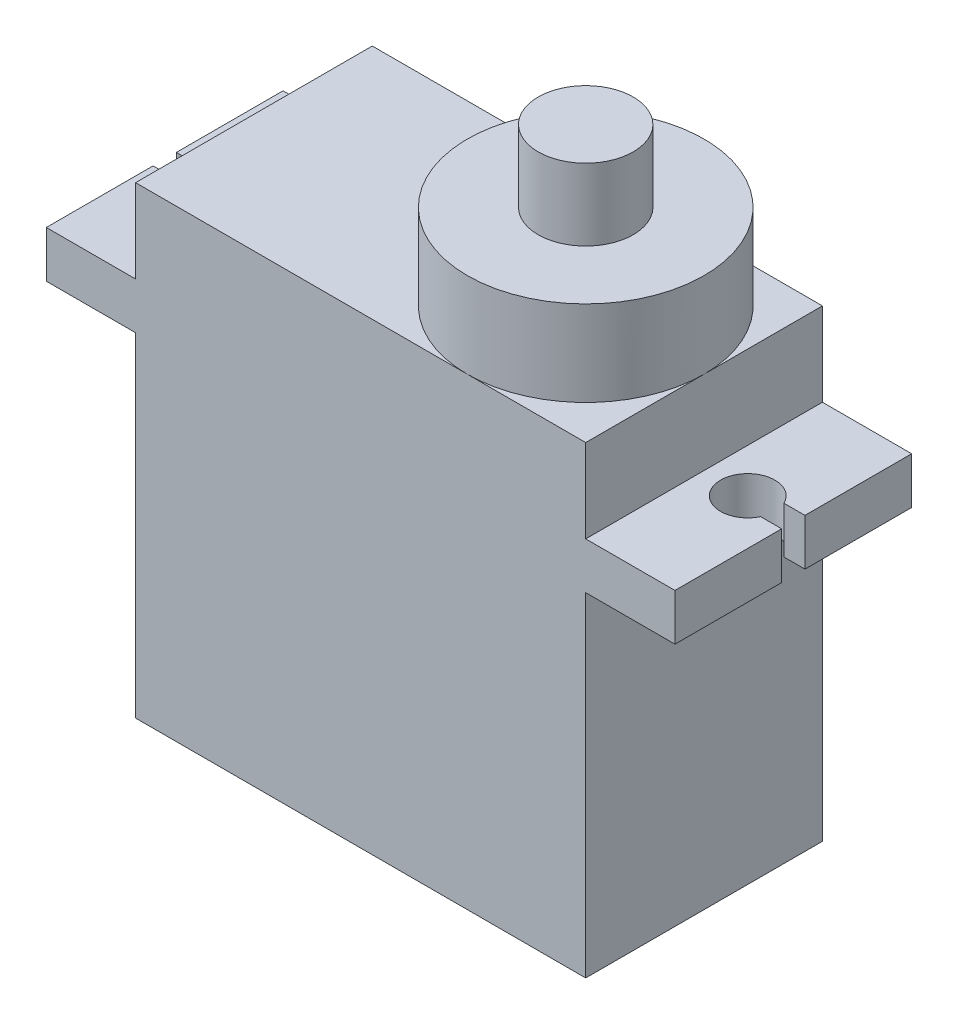
SolidWorks part; units mm, degrees
ref_plane "Front Plane" through (0, 0, 0) normal (0, 0, 1) x (1, 0, 0)
ref_plane "Top Plane" through (0, 0, 0) normal (0, 1, 0) x (1, 0, 0)
ref_plane "Right Plane" through (0, 0, 0) normal (1, 0, 0) x (0, 0, -1)
sketch "Sketch1" plane through (0, 0, 0) normal (0, 0, 1) x (1, 0, 0)
  line L1 (-4.0826, 11.0523) -> (19.1174, 11.0523)
  line L2 (-4.0826, 11.0523) -> (-4.0826, -6.1477)
  line L3 (-4.0826, -6.1477) -> (19.1174, -6.1477)
  line L4 (19.1174, 11.0523) -> (19.1174, -6.1477)
  dimension "D1" = 23.2
  dimension "D2" = 17.2
extrude "Boss-Extrude1" add sketch "Sketch1" along normal blind 12.2
sketch "Sketch2" plane through (0, 11.0523, 0) normal (0, 1, 0) x (1, 0, 0)
  line L0 (7.5174, 0) -> (7.5174, -12.2) construction
  line L1 (-8.6826, 0) -> (23.7174, 0)
  line L2 (-8.6826, 0) -> (-8.6826, -12.2)
  line L3 (-8.6826, -12.2) -> (23.7174, -12.2)
  line L4 (23.7174, 0) -> (23.7174, -12.2)
  line L5 (19.1174, 0) -> (-4.0826, 0) construction
  line L6 (19.1174, -12.2) -> (-4.0826, -12.2) construction
  point P11 (7.5174, -6.1)
  point P12 (7.5174, 0)
  point P13 (-8.6826, -6.1)
  dimension "D1" = 32.4
extrude "Boss-Extrude2" add sketch "Sketch2" along normal blind 2.4
sketch "Sketch3" plane through (0, 13.4523, 0) normal (0, 1, 0) x (1, 0, 0)
  line L0 (7.5174, 0) -> (7.5174, -12.2) construction
  line L1 (23.7174, 0) -> (-8.6826, 0) construction
  line L2 (-8.6826, -12.2) -> (23.7174, -12.2) construction
  line L3 (22.6324, -6.7) -> (23.9144, -6.7)
  line L4 (23.9144, -6.7) -> (23.9144, -5.5)
  line L5 (23.9144, -5.5) -> (22.6324, -5.5)
  line L6 (-8.8795, -5.5) -> (-7.5975, -5.5)
  line L7 (-8.8795, -6.7) -> (-8.8795, -5.5)
  line L8 (-7.5975, -6.7) -> (-8.8795, -6.7)
  arc A0 (22.6324, -5.5) -> (22.6324, -6.7) centre (21.3674, -6.1) ccw
  arc A3 (-7.5975, -5.5) -> (-7.5975, -6.7) centre (-6.3326, -6.1) cw
  point P9 (7.5174, -6.1)
  point P11 (23.9144, -6.1)
  dimension "D2" = 2.8
  dimension "D1" = 1.2
  dimension "D3" = 27.7
extrude "Cut-Extrude2" cut sketch "Sketch3" against normal up to surface (2.4 mm away) up to face at (21.4174, 11.0523, 6.1)
sketch "Sketch4" plane through (0, 13.4523, 0) normal (0, 1, 0) x (1, 0, 0)
  line L4 (19.1174, 0) -> (-4.0826, 0)
  line L5 (19.1174, -12.2) -> (19.1174, 0)
  line L6 (-4.0826, -12.2) -> (19.1174, -12.2)
  line L7 (-4.0826, 0) -> (-4.0826, -12.2)
  line L8 (19.1174, 0) -> (-4.0826, 0)
  line L9 (19.1174, -12.2) -> (19.1174, 0)
  line L10 (-4.0826, -12.2) -> (19.1174, -12.2)
  line L11 (-4.0826, 0) -> (-4.0826, -12.2)
  dimension "D1" = 0
extrude "Boss-Extrude3" add sketch "Sketch4" along normal blind 4.3
sketch "Sketch5" plane through (0, 17.7523, 0) normal (0, 1, 0) x (1, 0, 0)
  line L0 (19.1174, -12.2) -> (19.1174, 0) construction
  line L1 (19.1174, 0) -> (-4.0826, 0) construction
  line L2 (-4.0826, -12.2) -> (19.1174, -12.2) construction
  circle A0 centre (13.0174, -6.1) radius 6.1
extrude "Boss-Extrude4" add sketch "Sketch5" along normal blind 4.4
sketch "Sketch6" plane through (0, 22.1523, 0) normal (0, 1, 0) x (1, 0, 0)
  circle A0 centre (13.0174, -6.1) radius 2.45
  dimension "D1" = 4.9
extrude "Boss-Extrude5" add sketch "Sketch6" along normal blind 3.7
